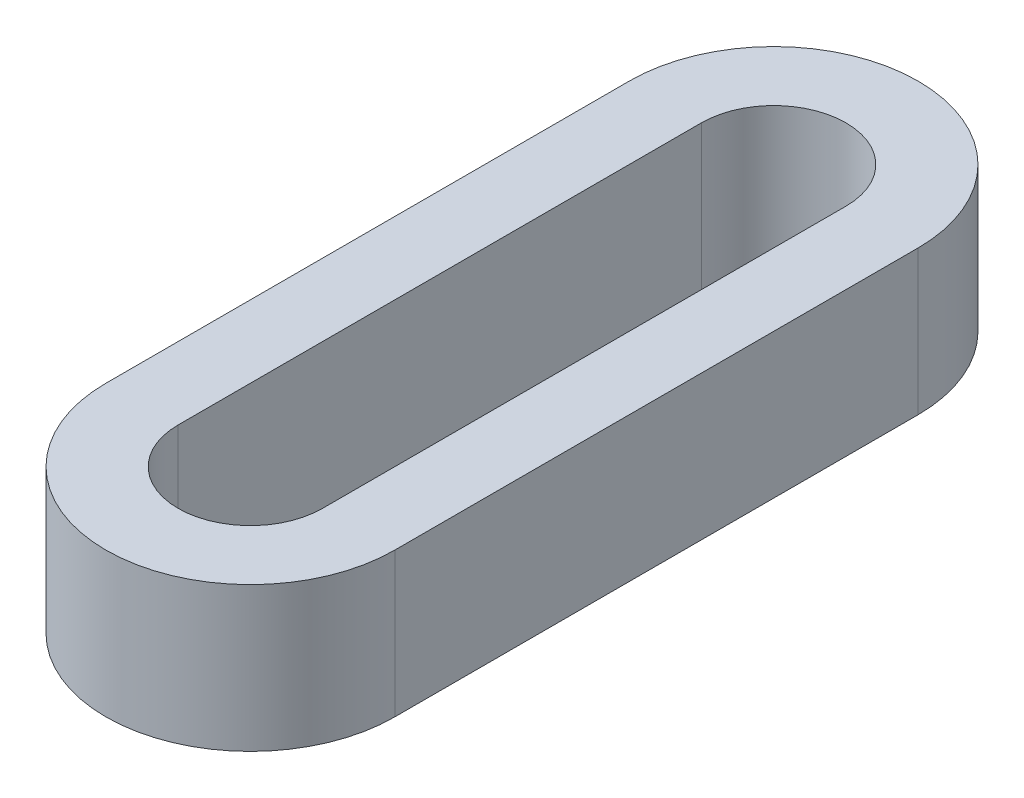
SolidWorks part; units mm, degrees
ref_plane "Front" through (0, 0, 0) normal (0, 0, 1) x (1, 0, 0)
ref_plane "Top" through (0, 0, 0) normal (0, 1, 0) x (1, 0, 0)
ref_plane "Right" through (0, 0, 0) normal (1, 0, 0) x (0, 0, -1)
sketch "Sketch1" plane through (0, 0, 0) normal (0, 1, 0) x (1, 0, 0)
  line L0 (0, -9.0565) -> (0, 9.0565) construction
  line L1 (-5, -9.0565) -> (5, -9.0565) construction
  line L2 (-5, -9.0565) -> (-5, 9.0565)
  line L3 (-5, 9.0565) -> (5, 9.0565) construction
  line L4 (5, -9.0565) -> (5, 9.0565)
  line L5 (-5, -9.0565) -> (5, 9.0565) construction
  line L6 (-5, 9.0565) -> (5, -9.0565) construction
  line L7 (-2.5, -9.0565) -> (-2.5, 9.0565)
  line L8 (2.5, -9.0565) -> (2.5, 9.0565)
  arc A0 (-5, 9.0565) -> (5, 9.0565) centre (0, 9.0565) cw
  arc A1 (-5, -9.0565) -> (5, -9.0565) centre (0, -9.0565) ccw
  arc A4 (-2.5, -9.0565) -> (2.5, -9.0565) centre (0, -9.0565) ccw
  arc A5 (2.5, 9.0565) -> (-2.5, 9.0565) centre (0, 9.0565) ccw
  point P0 (0, 0)
  point P9 (0, 0)
  dimension "D1" = 2.5
  dimension "D2" = 10
  dimension "D3" = 18.113
extrude "Boss-Extrude1" add sketch "Sketch1" along normal blind 5
